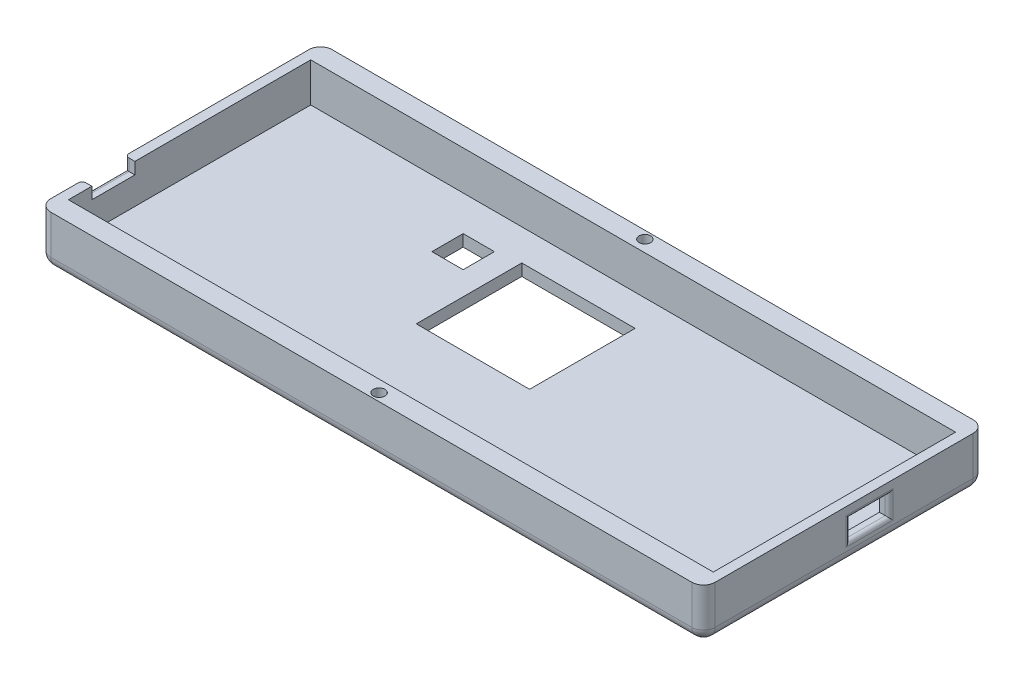
SolidWorks part; units mm, degrees
ref_plane "前视基准面" through (0, 0, 0) normal (0, 0, 1) x (1, 0, 0)
ref_plane "上视基准面" through (0, 0, 0) normal (0, 1, 0) x (1, 0, 0)
ref_plane "右视基准面" through (0, 0, 0) normal (1, 0, 0) x (0, 0, -1)
other "Configuration Table"
sketch "草图1" plane through (0, 0, 0) normal (0, 1, 0) x (1, 0, 0)
  line L1 (-85, -36) -> (85, -36)
  line L2 (-85, -36) -> (-85, 36)
  line L3 (-85, 36) -> (85, 36)
  line L4 (85, -36) -> (85, 36)
  line L5 (-85, -36) -> (85, 36) construction
  line L6 (-85, 36) -> (85, -36) construction
  point P0 (0, 0)
  dimension "D1" = 170
  dimension "D2" = 72
extrude "凸台-拉伸1" add sketch "草图1" along normal blind 3
sketch "草图2" plane through (0, 3, 0) normal (0, 1, 0) x (1, 0, 0)
  line L1 (-82.5, -31) -> (82.5, -31)
  line L2 (-82.5, -31) -> (-82.5, 31)
  line L3 (-82.5, 31) -> (82.5, 31)
  line L4 (85, -36) -> (85, 36)
  line L5 (85, 36) -> (-85, 36)
  line L6 (-85, 36) -> (-85, -36)
  line L7 (-85, -36) -> (85, -36)
  line L8 (85, -36) -> (85, 36)
  line L9 (85, 36) -> (-85, 36)
  line L10 (-85, 36) -> (-85, -36)
  line L11 (-85, -36) -> (85, -36)
  line L12 (82.5, -31) -> (82.5, 31)
  line L13 (-82.5, -31) -> (82.5, 31) construction
  line L14 (-82.5, 31) -> (82.5, -31) construction
  point P2 (0, 0)
  dimension "D2" = 2.5
  dimension "D3" = 5
  dimension "D1" = 0
extrude "凸台-拉伸2" add sketch "草图2" along normal blind 10
sketch "草图3" plane through (0, 13, 0) normal (0, 1, 0) x (1, 0, 0)
  line L1 (85, 36) -> (-85, 36) construction
  line L2 (-85, -36) -> (85, -36) construction
  circle A0 centre (0, 34) radius 1.5
  circle A1 centre (0, -34) radius 1.5
  dimension "D1" = 3
  dimension "D2" = 3
  dimension "D3" = 2
  dimension "D4" = 2
extrude "切除-拉伸1" cut sketch "草图3" against normal blind 3
sketch "草图4" plane through (0, 0, 0) normal (0, -1, 0) x (1, 0, 0)
  line L0 (85, -36) -> (-85, -36) construction
  line L1 (-20.5, 4) -> (8.5, 4)
  line L2 (-20.5, 4) -> (-20.5, -23)
  line L3 (-20.5, -23) -> (8.5, -23)
  line L4 (8.5, 4) -> (8.5, -23)
  line L5 (-26.5, -14) -> (-34.5, -14)
  line L6 (-26.5, -14) -> (-26.5, -22)
  line L7 (-26.5, -22) -> (-34.5, -22)
  line L8 (-34.5, -14) -> (-34.5, -22)
  line L9 (-85, -36) -> (-85, 36) construction
  dimension "D1" = 13
  dimension "D2" = 40
  dimension "D3" = 64.5
  dimension "D4" = 93.5
  dimension "D5" = 14
  dimension "D6" = 22
  dimension "D7" = 58.5
  dimension "D8" = 50.5
extrude "切除-拉伸2" cut sketch "草图4" against normal blind 3 contours L6 L5 L8 L7 | L2 L1 L4 L3
fillet "圆角1" radius 3 8 edges at (85, 0, 0) (0, 0, 36) (-85, 0, 0) (0, 0, -36) (-85, 6.5, 36) (-85, 6.5, -36) (85, 6.5, -36) (85, 6.5, 36)
sketch "草图5" plane through (-85, 0, 0) normal (-1, 0, 0) x (0, 0, 1)
  line L0 (33, 0) -> (-33, 0) construction
  line L1 (14, 13) -> (25, 13)
  line L2 (14, 13) -> (14, 10)
  line L3 (14, 10) -> (25, 10)
  line L4 (25, 13) -> (25, 10)
  line L5 (36, 13) -> (36, 3) construction
  dimension "D1" = 10
  dimension "D2" = 13
  dimension "D3" = 22
  dimension "D4" = 11
extrude "切除-拉伸3" cut sketch "草图5" against normal blind 3
fillet "圆角3" radius 1 3 edges at (-85, 11.5, 25) (-85, 10, 19.5) (-85, 11.5, 14)
sketch "草图6" plane through (85, 0, 0) normal (1, 0, 0) x (0, 0, -1)
  line L0 (36, 13) -> (36, 3) construction
  line L1 (1.5, 10) -> (11.5, 10)
  line L2 (1.5, 10) -> (1.5, 5)
  line L3 (1.5, 5) -> (11.5, 5)
  line L4 (11.5, 10) -> (11.5, 5)
  line L5 (33, 0) -> (-33, 0) construction
  dimension "D1" = 24.5
  dimension "D2" = 34.5
  dimension "D3" = 5
  dimension "D4" = 10
extrude "切除-拉伸4" cut sketch "草图6" against normal blind 3
fillet "圆角4" radius 1 4 edges at (85, 5, -6.5) (85, 7.5, -11.5) (85, 7.5, -1.5) (85, 10, -6.5)
